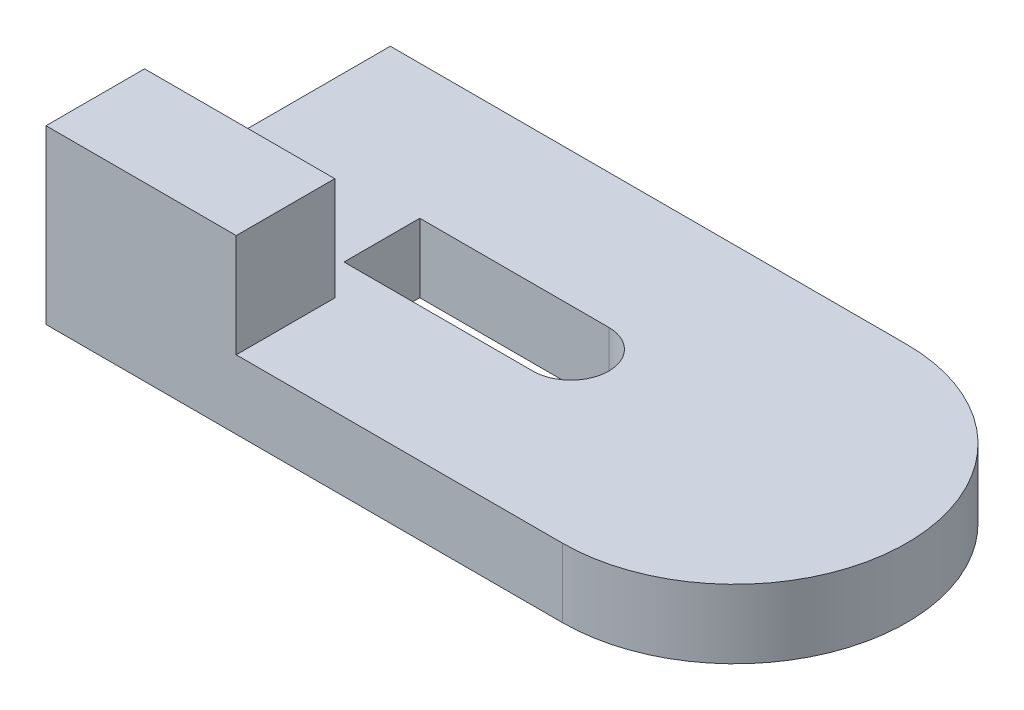
SolidWorks part; units mm, degrees
ref_plane "Front Plane" through (0, 0, 0) normal (0, 0, 1) x (1, 0, 0)
ref_plane "Top Plane" through (0, 0, 0) normal (0, 1, 0) x (1, 0, 0)
ref_plane "Right Plane" through (0, 0, 0) normal (1, 0, 0) x (0, 0, -1)
sketch "Sketch1" plane through (0, 0, 0) normal (0, 1, 0) x (1, 0, 0)
  line L1 (-75, 50) -> (75, 50)
  line L2 (-75, 50) -> (-75, -50)
  line L3 (-75, -50) -> (75, -50)
  line L5 (-75, 50) -> (75, -50) construction
  line L6 (-75, -50) -> (75, 50) construction
  arc A0 (75, -50) -> (75, 50) centre (75, 0) ccw
  point P0 (0, 0)
  dimension "D1" = 150
  dimension "D2" = 100
extrude "Boss-Extrude1" add sketch "Sketch1" along normal blind 20
sketch "Sketch2" plane through (0, 20, 0) normal (0, 1, 0) x (1, 0, 0)
  line L1 (-75, -50) -> (-19.7456, -50)
  line L2 (-75, -50) -> (-75, -21.3812)
  line L3 (-75, -21.3812) -> (-19.7456, -21.3812)
  line L4 (-19.7456, -50) -> (-19.7456, -21.3812)
extrude "Boss-Extrude5" add sketch "Sketch2" along normal blind 30
sketch "Sketch3" plane through (0, 20, 0) normal (0, 1, 0) x (1, 0, 0)
  line L1 (-27.4435, 11.0089) -> (27.4435, 11.0089)
  line L2 (-27.4435, 11.0089) -> (-27.4435, -11.0089)
  line L3 (-27.4435, -11.0089) -> (27.4435, -11.0089)
  line L4 (27.4435, 11.0089) -> (27.4435, -11.0089)
  line L5 (-27.4435, 11.0089) -> (27.4435, -11.0089) construction
  line L6 (-27.4435, -11.0089) -> (27.4435, 11.0089) construction
  circle A0 centre (27.4435, 0) radius 11.0089
  point P0 (0, 0)
extrude "Cut-Extrude1" cut sketch "Sketch3" against normal blind 30 contours A0 L1 L2 L3
